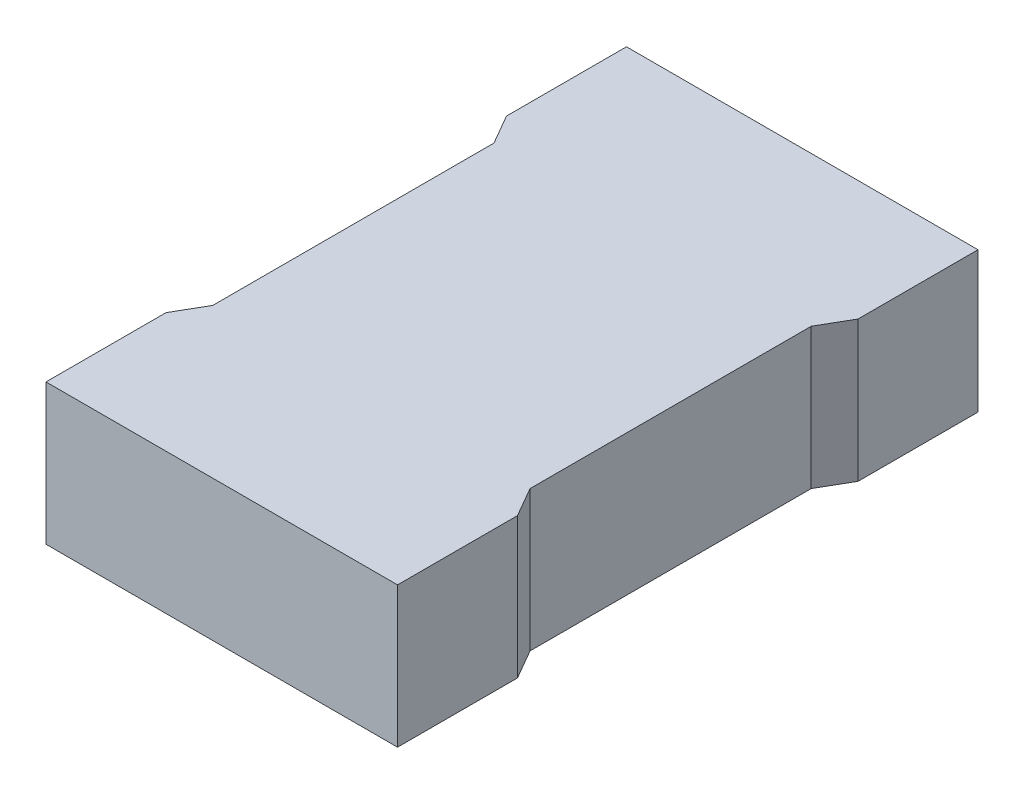
SolidWorks part; units mm, degrees
ref_plane "Front Plane" through (0, 0, 0) normal (0, 0, 1) x (1, 0, 0)
ref_plane "Top Plane" through (0, 0, 0) normal (0, 1, 0) x (1, 0, 0)
ref_plane "Right Plane" through (0, 0, 0) normal (1, 0, 0) x (0, 0, -1)
sketch "Sketch2" plane through (0, 0, 0) normal (0, 1, 0) x (1, 0, 0)
  line L0 (-22.352, 0) -> (22.352, 0) construction
  line L1 (24.765, -40.894) -> (-24.765, -40.894)
  line L2 (24.765, -40.894) -> (24.765, -23.9914)
  line L3 (24.765, 40.894) -> (-24.765, 40.894)
  line L4 (-24.765, -40.894) -> (-24.765, -23.9914)
  line L5 (24.765, -40.894) -> (-24.765, 40.894) construction
  line L6 (24.765, 40.894) -> (-24.765, -40.894) construction
  line L7 (0, 40.894) -> (0, -40.894) construction
  line L8 (-24.765, 23.9914) -> (-22.352, 19.812)
  line L9 (-22.352, 19.812) -> (-22.352, -19.812)
  line L10 (-24.765, -23.9914) -> (-22.352, -19.812)
  line L11 (24.765, -23.9914) -> (22.352, -19.812)
  line L12 (22.352, 19.812) -> (22.352, -19.812)
  line L13 (24.765, 23.9914) -> (22.352, 19.812)
  line L14 (-24.765, 23.9914) -> (-24.765, 40.894)
  line L15 (24.765, 23.9914) -> (24.765, 40.894)
  point P0 (0, 0)
  point P14 (-22.352, 0)
  point P19 (22.86, 0)
  point P20 (0, 0)
  point P21 (-22.352, 0)
  point P22 (-22.86, 0)
  point P23 (22.352, 0)
  point P25 (0, 0)
  dimension "D1" = 81.788
  dimension "D2" = 49.53
  dimension "D3" = 44.704
  dimension "D4" = 150
  dimension "D5" = 39.624
extrude "Boss-Extrude2" add sketch "Sketch2" along normal blind 19.812 separate body
